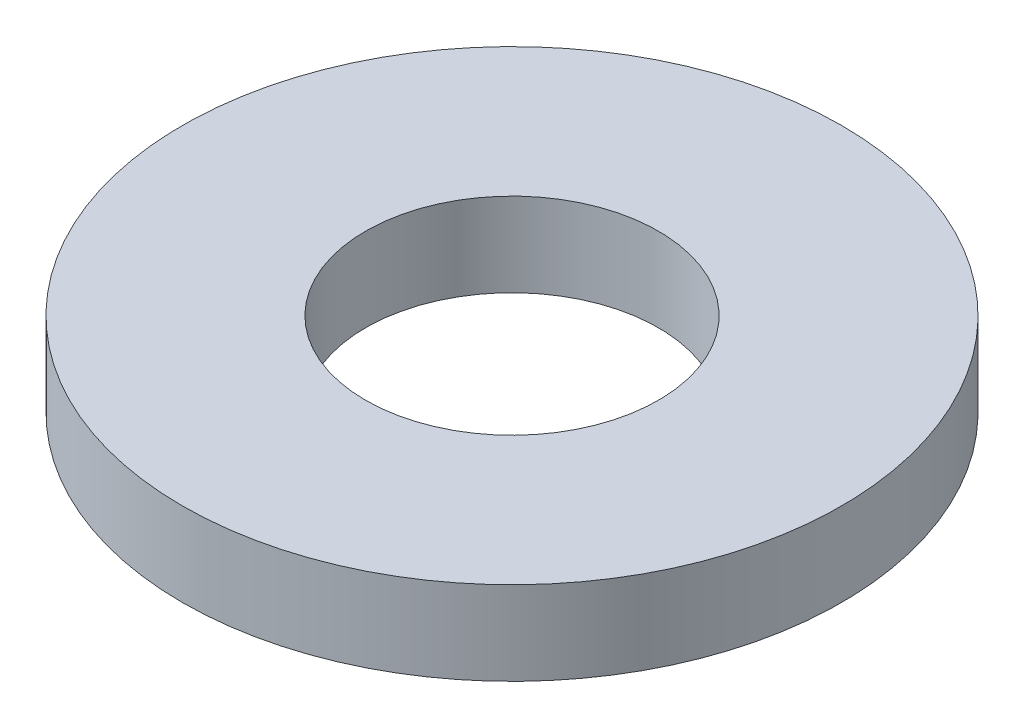
SolidWorks part; units mm, degrees
ref_plane "Front Plane" through (0, 0, 0) normal (0, 0, 1) x (1, 0, 0)
ref_plane "Top Plane" through (0, 0, 0) normal (0, 1, 0) x (1, 0, 0)
ref_plane "Right Plane" through (0, 0, 0) normal (1, 0, 0) x (0, 0, -1)
sketch "Sketch1" plane through (0, 0, 0) normal (0, 1, 0) x (1, 0, 0)
  circle A0 centre (0, 0) radius 8.001
  dimension "OD" = 16.002
extrude "Boss-Extrude1" add sketch "Sketch1" along normal blind 2.032
sketch "Sketch5" plane through (0, 2.032, 0) normal (0, 1, 0) x (-1, 0, 0)
  circle A0 centre (0, 0) radius 3.556
  dimension "ID" = 7.112
extrude "Cut-Extrude1" cut sketch "Sketch5" against normal through all
